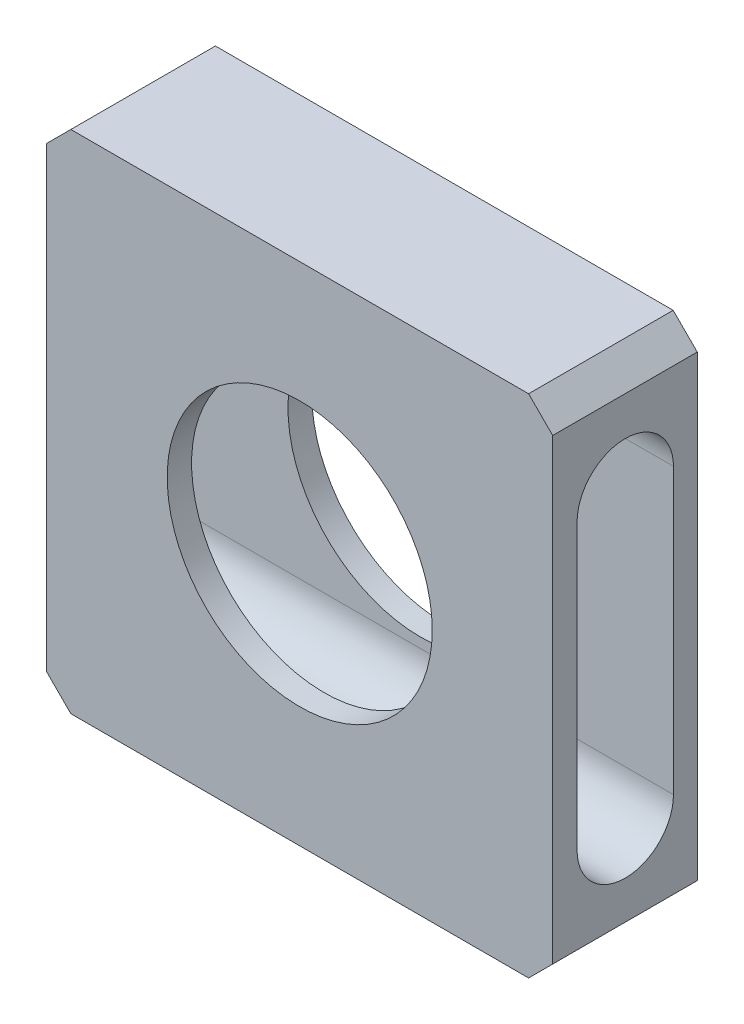
SolidWorks part; units mm, degrees
material "PVC rigido"
ref_plane "Piano frontale" through (0, 0, 0) normal (0, 0, 1) x (1, 0, 0)
ref_plane "Piano superiore" through (0, 0, 0) normal (0, 1, 0) x (1, 0, 0)
ref_plane "Piano destro" through (0, 0, 0) normal (1, 0, 0) x (0, 0, -1)
sketch "Schizzo2" plane through (0, 0, 0) normal (0, 0, 1) x (1, 0, 0)
  line L4 (21, 21) -> (21, -21)
  line L5 (21, -21) -> (-21, -21)
  line L6 (-21, -21) -> (-21, 21)
  line L7 (-21, 21) -> (21, 21)
sketch "Schizzo3" plane through (0, 0, 0) normal (0, 0, 1) x (1, 0, 0)
  circle A0 centre (0, 0) radius 11
extrude "Estrusione-Estrusione1" add sketch "Schizzo2" along normal blind 12 contours L7 L4 L5 L6
extrude "Taglio-Estrusione1" cut sketch "Schizzo3" along normal blind 12 contours A0
sketch "Schizzo5" plane through (21, 0, 0) normal (1, 0, 0) x (0, 0, -1)
  line L0 (-5.9761, 11.7702) -> (-5.9761, -11.8298) construction
  line L1 (-1.9761, 11.7702) -> (-1.9761, -11.8298)
  line L2 (-9.9761, 11.7702) -> (-9.9761, -11.8298)
  arc A0 (-1.9761, 11.7702) -> (-9.9761, 11.7702) centre (-5.9761, 11.7702) ccw
  arc A1 (-9.9761, -11.8298) -> (-1.9761, -11.8298) centre (-5.9761, -11.8298) ccw
  point P2 (-5.9761, -0.0298)
extrude "Taglio-Estrusione2" cut sketch "Schizzo5" against normal blind 42 contours L1 A1 L2 A0
chamfer "Smusso2" distance 2 angle 45 1 edges at (-21, 21, 6)
chamfer "Smusso3" distance 2 angle 45 1 edges at (21, 21, 6)
chamfer "Smusso4" distance 2 angle 45 1 edges at (21, -21, 6)
chamfer "Smusso5" distance 2 angle 45 1 edges at (-21, -21, 6)
